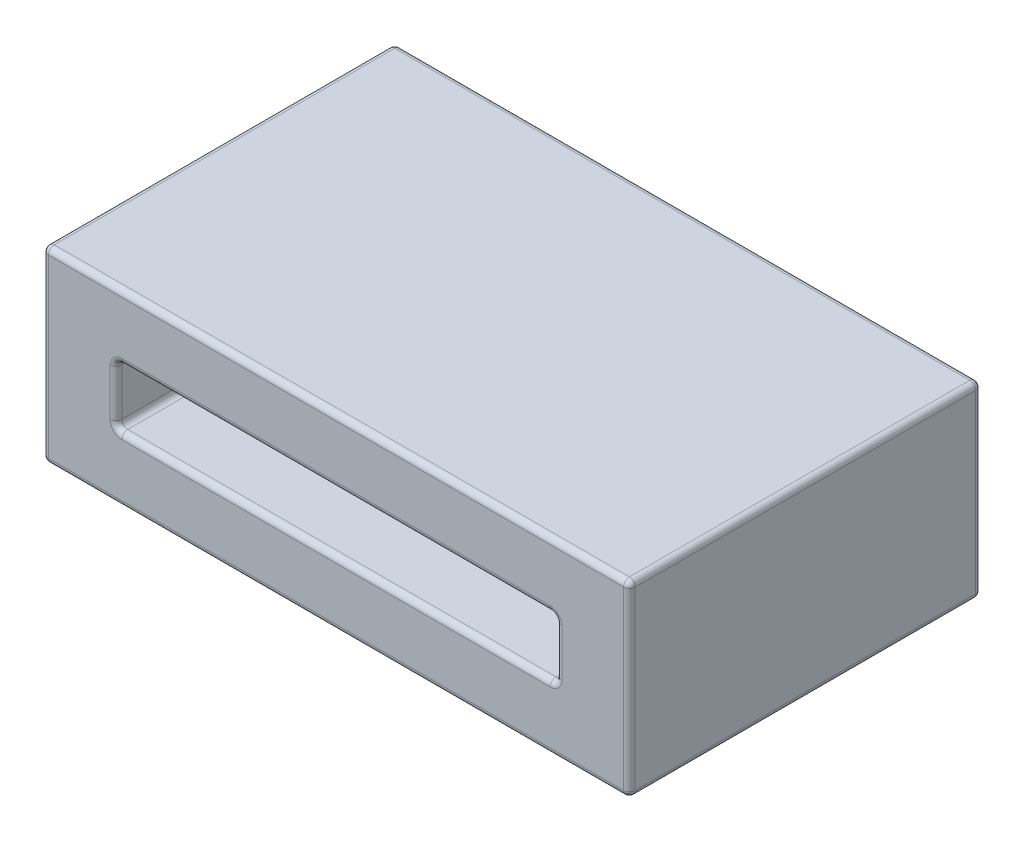
SolidWorks part; units mm, degrees
ref_plane "Front Plane" through (0, 0, 0) normal (0, 0, 1) x (1, 0, 0)
ref_plane "Top Plane" through (0, 0, 0) normal (0, 1, 0) x (1, 0, 0)
ref_plane "Right Plane" through (0, 0, 0) normal (1, 0, 0) x (0, 0, -1)
sketch "Sketch1" plane through (0, 0, 0) normal (0, 1, 0) x (1, 0, 0)
  line L1 (-50, 30) -> (50, 30)
  line L2 (-50, 30) -> (-50, -30)
  line L3 (-50, -30) -> (50, -30)
  line L4 (50, 30) -> (50, -30)
  line L5 (-50, 30) -> (50, -30) construction
  line L6 (-50, -30) -> (50, 30) construction
  point P0 (0, 0)
  dimension "D1" = 100
  dimension "D2" = 60
extrude "Boss-Extrude1" add sketch "Sketch1" along normal blind 32
sketch "Sketch2" plane through (0, 0, 30) normal (0, 0, 1) x (1, 0, 0)
  line L0 (-50, 32) -> (-50, 0) construction
  line L1 (-37.5, 21) -> (37.5, 21)
  line L2 (-37.5, 21) -> (-37.5, 11)
  line L3 (-37.5, 11) -> (37.5, 11)
  line L4 (37.5, 21) -> (37.5, 11)
  point P4 (0, 11)
  point P8 (-50, 16)
  point P9 (-37.5, 16)
  dimension "D1" = 75
  dimension "D2" = 10
extrude "Cut-Extrude1" cut sketch "Sketch2" against normal through all
fillet "Fillet2" radius 1 24 edges at (0, 0, -30) (37.5, 16, -30) (-37.5, 16, -30) (50, 16, -30) (50, 0, 0) (37.5, 21, 0) (0, 21, -30) (-37.5, 21, 0) (-37.5, 11, 0) (0, 11, -30) (37.5, 11, 0) (-50, 16, -30) (-50, 0, 0) (-50, 16, 30) (50, 16, 30) (0, 0, 30) (37.5, 16, 30) (0, 21, 30) (-37.5, 16, 30) (0, 11, 30) (0, 32, 30) (-50, 32, 0) (0, 32, -30) (50, 32, 0)
